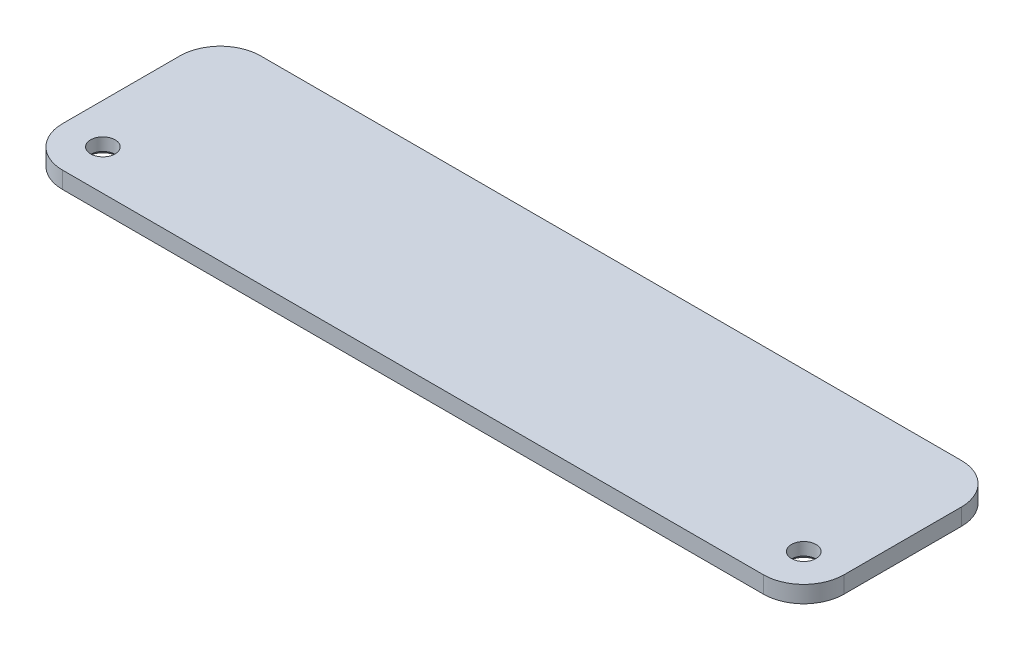
SolidWorks part; units mm, degrees
ref_plane "Front Plane" through (0, 0, 0) normal (0, 0, 1) x (1, 0, 0)
ref_plane "Top Plane" through (0, 0, 0) normal (0, 1, 0) x (1, 0, 0)
ref_plane "Right Plane" through (0, 0, 0) normal (1, 0, 0) x (0, 0, -1)
sketch "Sketch1" plane through (0, 0, 0) normal (0, 1, 0) x (1, 0, 0)
  line L0 (-55.75, 23.25) -> (55.75, 23.25) construction
  line L1 (-50, 28.25) -> (50, 28.25)
  line L2 (-55.75, 22.5) -> (-55.75, 5.75)
  line L3 (-50, 0) -> (50, 0)
  line L4 (55.75, 22.5) -> (55.75, 5.75)
  line L6 (-50, 105.75) -> (50, 105.75) construction
  line L7 (-50, 105.75) -> (-50, 5.75) construction
  line L8 (-50, 5.75) -> (50, 5.75) construction
  line L9 (50, 105.75) -> (50, 5.75) construction
  line L10 (-50, 105.75) -> (50, 5.75) construction
  line L11 (-50, 5.75) -> (50, 105.75) construction
  arc A0 (-55.75, 5.75) -> (-50, 0) centre (-50, 5.75) ccw
  arc A1 (50, 0) -> (55.75, 5.75) centre (50, 5.75) ccw
  circle A2 centre (-50, 5.75) radius 1.75
  circle A3 centre (50, 5.75) radius 1.75
  arc A4 (50, 28.25) -> (55.75, 22.5) centre (50, 22.5) cw
  arc A5 (-50, 28.25) -> (-55.75, 22.5) centre (-50, 22.5) ccw
  point P6 (0, 55.75)
  dimension "D1" = 3.5
  dimension "D5" = 4
  dimension "D2" = 100
  dimension "D3" = 32.5
  dimension "D4" = 5
extrude "Boss-Extrude1" add sketch "Sketch1" along normal blind 2.4
chamfer "Chamfer1" distance 0.6 angle 45 2 edges at (50, 0, -4) (-50, 0, -4)
